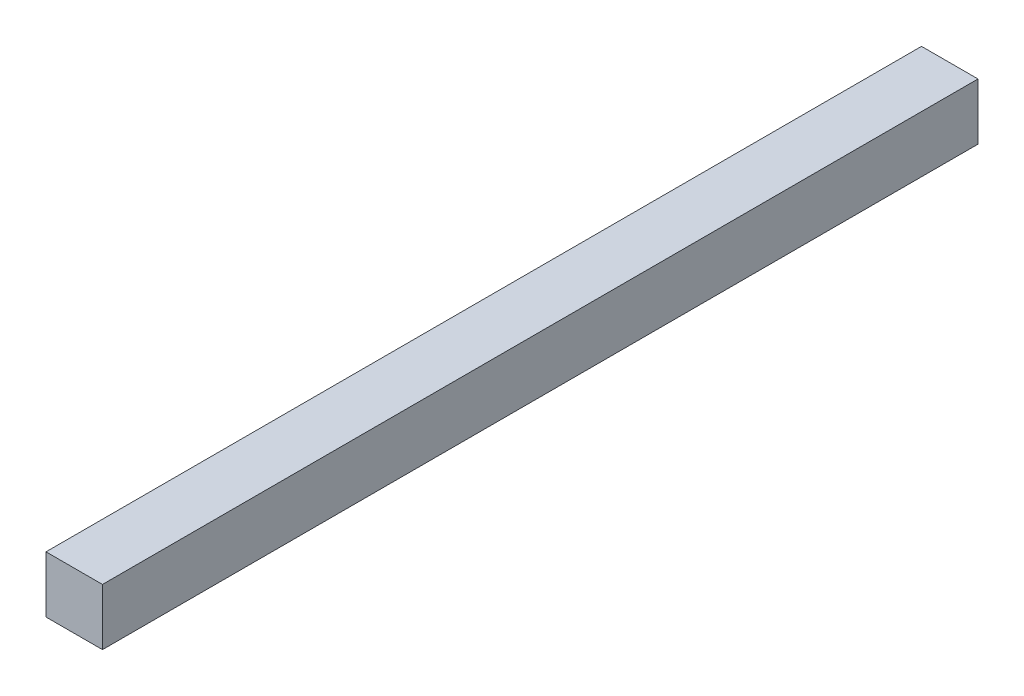
SolidWorks part; units mm, degrees
ref_plane "Plan de face" through (0, 0, 0) normal (0, 0, 1) x (1, 0, 0)
ref_plane "Plan de dessus" through (0, 0, 0) normal (0, 1, 0) x (1, 0, 0)
ref_plane "Plan de droite" through (0, 0, 0) normal (1, 0, 0) x (0, 0, -1)
sketch "Esquisse1" plane through (0, 0, 0) normal (0, 0, 1) x (1, 0, 0)
  line L1 (0, 0) -> (40, 0)
  line L2 (0, 0) -> (0, 40)
  line L3 (0, 40) -> (40, 40)
  line L4 (40, 0) -> (40, 40)
  dimension "D1" = 40
  dimension "D2" = 40
extrude "Boss.-Extru.1" add sketch "Esquisse1" along normal blind 620
